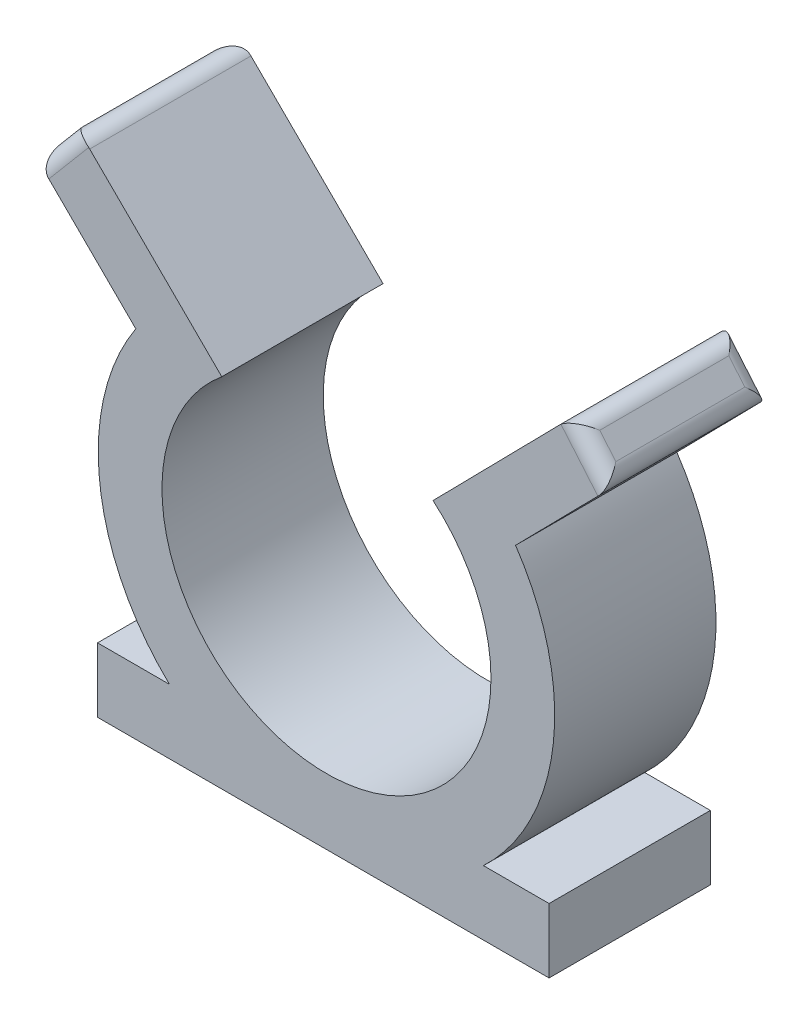
SolidWorks part; units mm, degrees
ref_plane "Front Plane" through (0, 0, 0) normal (0, 0, 1) x (1, 0, 0)
ref_plane "Top Plane" through (0, 0, 0) normal (0, 1, 0) x (1, 0, 0)
ref_plane "Right Plane" through (0, 0, 0) normal (1, 0, 0) x (0, 0, -1)
sketch "Sketch1" plane through (0, 0, 0) normal (0, 1, 0) x (1, 0, 0)
  line L1 (-14, 5) -> (14, 5)
  line L2 (-14, 5) -> (-14, -5)
  line L3 (-14, -5) -> (14, -5)
  line L4 (14, 5) -> (14, -5)
  line L5 (-14, 5) -> (14, -5) construction
  line L6 (-14, -5) -> (14, 5) construction
  point P0 (0, 0)
extrude "Boss-Extrude1" add sketch "Sketch1" along normal blind 4
sketch "Sketch3" plane through (0, 0, 0) normal (0, 0, 1) x (1, 0, 0)
  line L0 (6.8049, 22.0431) -> (15.435, 30.8241)
  line L2 (15.435, 30.8241) -> (17.7299, 28.1079)
  line L3 (11.9216, 22.198) -> (17.7299, 28.1079)
  line L4 (-6.2952, 22.1413) -> (-15.2557, 31.0363)
  line L6 (-15.2557, 31.0363) -> (-17.7299, 28.1079)
  line L7 (-11.6276, 22.0502) -> (-17.7299, 28.1079)
  arc A0 (-11.6276, 22.0502) -> (11.9216, 22.198) centre (0.1963, 14.2735) ccw
  arc A1 (-6.2952, 22.1413) -> (6.8049, 22.0431) centre (0.1963, 14.2735) ccw
extrude "Boss-Extrude2" add sketch "Sketch3" along normal blind 10 from offset 5 offset against normal yes
fillet "Fillet3" radius 1 8 edges at (17.7299, 28.1079, 0) (16.5825, 29.466, -5) (16.5825, 29.466, 5) (15.435, 30.8241, 0) (-15.2557, 31.0363, 0) (-16.4928, 29.5721, -5) (-16.4928, 29.5721, 5) (-17.7299, 28.1079, 0)
